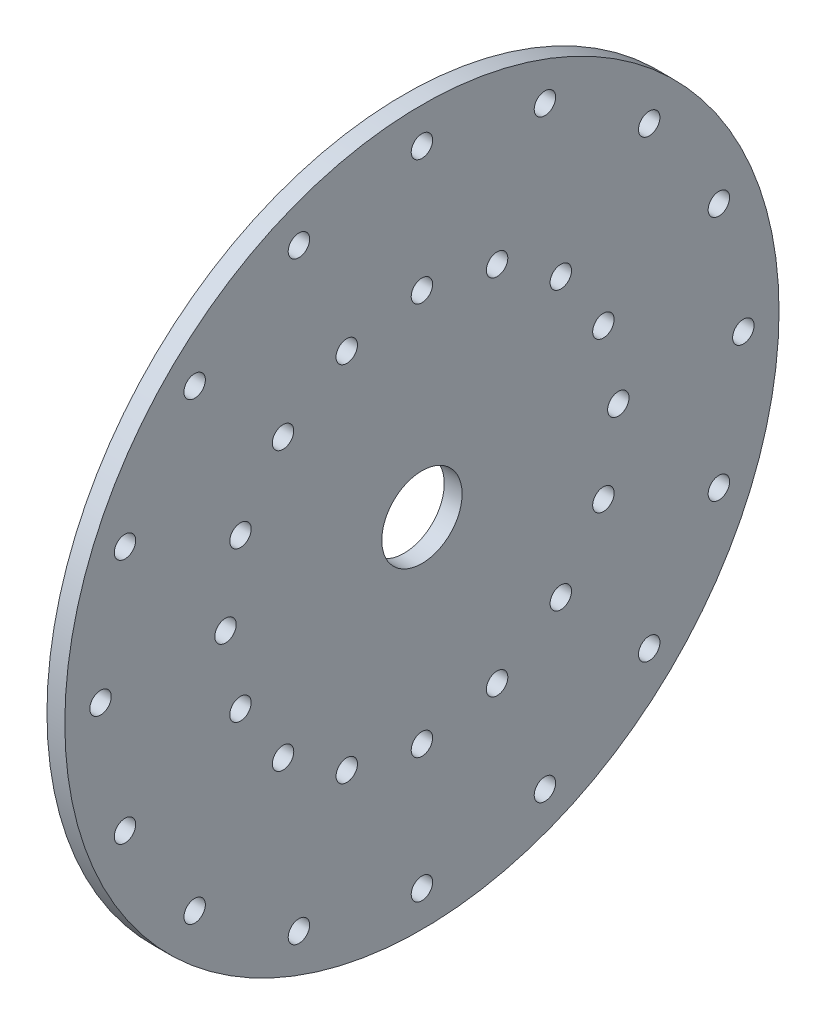
SolidWorks part; units mm, degrees
material "ASTM A36 Steel"
ref_plane "Front Plane" through (0, 0, 0) normal (0, 0, 1) x (1, 0, 0)
ref_plane "Top Plane" through (0, 0, 0) normal (0, 1, 0) x (1, 0, 0)
ref_plane "Right Plane" through (0, 0, 0) normal (1, 0, 0) x (0, 0, -1)
sketch "Sketch1" plane through (0, 0, 0) normal (1, 0, 0) x (0, 0, -1)
  circle A0 centre (0, 0) radius 200
  dimension "D1" = 400
extrude "Boss-Extrude1" add sketch "Sketch1" along normal blind 10
sketch "Sketch2" plane through (10, 0, 0) normal (1, 0, 0) x (0, 0, -1)
  circle A0 centre (0, 0) radius 22.5
  dimension "D1" = 45
extrude "Cut-Extrude1" cut sketch "Sketch2" against normal blind 10
sketch "Sketch3" plane through (10, 0, 0) normal (1, 0, 0) x (0, 0, -1)
  circle A1 centre (110, 0) radius 6
  dimension "D2" = 12
extrude "Cut-Extrude2" cut sketch "Sketch3" against normal blind 10
pattern_circular "CirPattern1" count 16 over 360 about axis through (0, 0, 0) along (1, 0, 0) of "Cut-Extrude2"
sketch "Sketch4" plane through (10, 0, 0) normal (1, 0, 0) x (0, 0, -1)
  circle A1 centre (180, 0) radius 6
  dimension "D1" = 12
extrude "Cut-Extrude3" cut sketch "Sketch4" against normal blind 10
pattern_circular "CirPattern2" count 16 over 360 about axis through (0, 0, 0) along (1, 0, 0) of "Cut-Extrude3"
